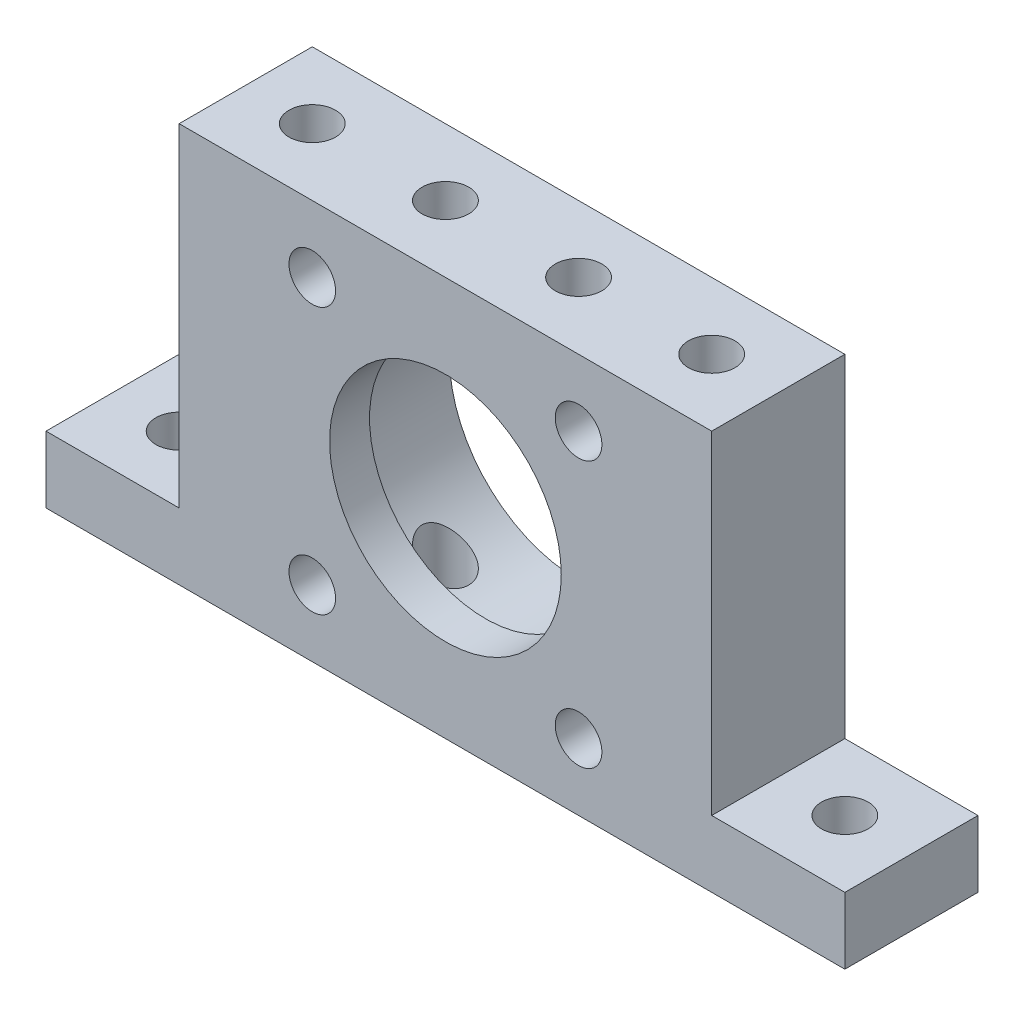
SolidWorks part; units mm, degrees
ref_plane "Plan de face" through (0, 0, 0) normal (0, 0, 1) x (1, 0, 0)
ref_plane "Plan de dessus" through (0, 0, 0) normal (0, 1, 0) x (1, 0, 0)
ref_plane "Plan de droite" through (0, 0, 0) normal (1, 0, 0) x (0, 0, -1)
sketch "Esquisse1" plane through (0, 0, 0) normal (0, 0, 1) x (1, 0, 0)
  line L0 (-20, -10) -> (-20, 15)
  line L1 (-20, 15) -> (20, 15)
  line L2 (20, 15) -> (20, -10)
  line L3 (20, -10) -> (-20, -10) construction
  line L4 (0, 26.751) -> (0, -33.9532) construction
  line L5 (-20, -10) -> (-30, -10)
  line L6 (-30, -10) -> (-30, -15)
  line L7 (-30, -15) -> (30, -15)
  line L8 (30, -15) -> (30, -10)
  line L9 (30, -10) -> (20, -10)
  line L10 (10, 10) -> (10, -10) construction
  circle A0 centre (0, 0) radius 9.7
  circle A1 centre (10, 10) radius 1.75
  circle A2 centre (-10, 10) radius 1.75
  circle A3 centre (-10, -10) radius 1.75
  circle A4 centre (10, -10) radius 1.75
  dimension "D1" = 19.4
  dimension "D10" = 3.5
  dimension "D2" = 15
  dimension "D3" = 10
  dimension "D4" = 40
  dimension "D5" = 10
  dimension "D6" = 25
  dimension "D7" = 5
  dimension "D8" = 5
  dimension "D9" = 10
  dimension "D13" = 20
  dimension "D11" = 2
  dimension "D12" = 2
extrude "Boss.-Extru.1" add sketch "Esquisse1" along normal blind 10
sketch "Esquisse2" plane through (0, 0, 10) normal (0, 0, 1) x (1, 0, 0)
  circle A0 centre (0, 0) radius 9.7
  circle A1 centre (0, 0) radius 8.7
  circle A2 centre (0, 0) radius 9.7 construction
  dimension "D1" = 1
extrude "Boss.-Extru.2" add sketch "Esquisse2" against normal offset from surface (3 mm away) 7 up to face at (0, -5, 0)
sketch "Esquisse3" plane through (0, -15, 0) normal (0, -1, 0) x (1, 0, 0)
  line L0 (-30, 5) -> (30, 5) construction
  line L1 (-30, 10) -> (-30, 0) construction
  line L2 (30, 10) -> (30, 0) construction
  circle A0 centre (-25, 5) radius 1.75
  circle A1 centre (-15, 5) radius 1.75
  circle A2 centre (-5, 5) radius 1.75
  circle A3 centre (5, 5) radius 1.75
  circle A4 centre (15, 5) radius 1.75
  circle A5 centre (25, 5) radius 1.75
  dimension "D2" = 3.5
  dimension "D1" = 5
  dimension "D3" = 6
extrude "Enlèv. mat.-Extru.1" cut sketch "Esquisse3" against normal through all
